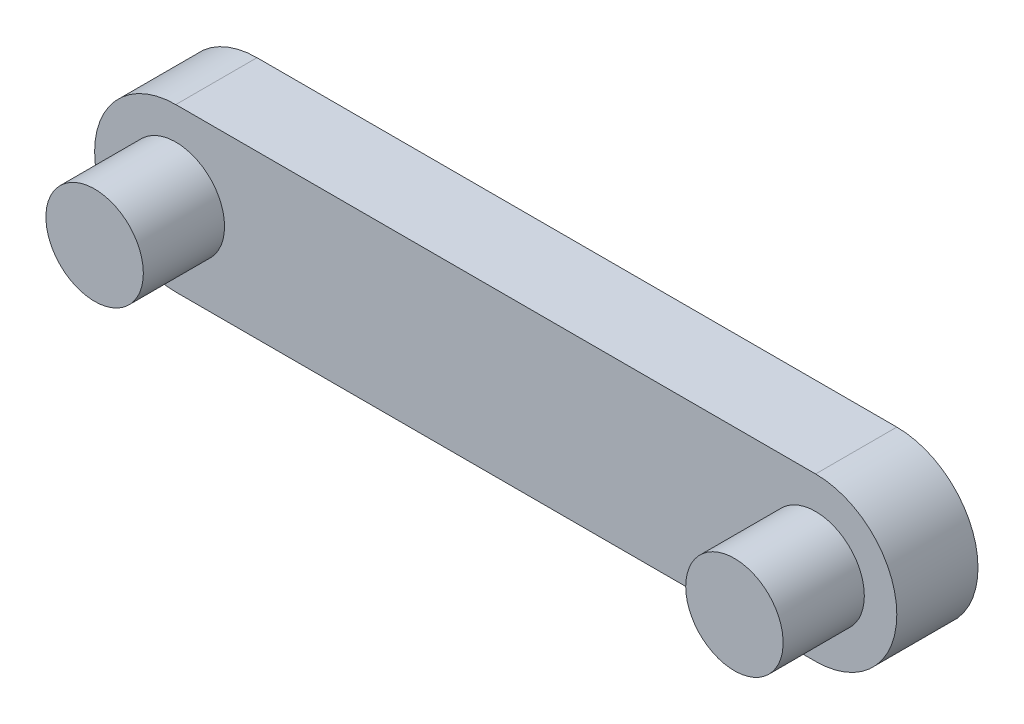
SolidWorks part; units mm, degrees
ref_plane "Front Plane" through (0, 0, 0) normal (0, 0, 1) x (1, 0, 0)
ref_plane "Top Plane" through (0, 0, 0) normal (0, 1, 0) x (1, 0, 0)
ref_plane "Right Plane" through (0, 0, 0) normal (1, 0, 0) x (0, 0, -1)
sketch "Sketch1" plane through (0, 0, 0) normal (0, 0, 1) x (1, 0, 0)
  line L0 (19.7, 0) -> (-19.7, 0) construction
  line L1 (19.7, -5) -> (-19.7, -5)
  line L2 (19.7, 5) -> (-19.7, 5)
  arc A0 (19.7, -5) -> (19.7, 5) centre (19.7, 0) ccw
  arc A1 (-19.7, 5) -> (-19.7, -5) centre (-19.7, 0) ccw
  circle A2 centre (19.7, 0) radius 3
  point P2 (0, 0)
  dimension "D2" = 5
  dimension "D3" = 6
  dimension "D1" = 39.4
extrude "Boss-Extrude1" add sketch "Sketch1" along normal blind 5
sketch "Sketch2" plane through (0, 0, 5) normal (0, 0, 1) x (1, 0, 0)
  circle A0 centre (-19.7, 0) radius 3
  dimension "D1" = 6
extrude "Boss-Extrude2" add sketch "Sketch2" along normal blind 5
sketch "Sketch3" plane through (0, 0, 0) normal (0, 0, -1) x (-1, 0, 0)
  circle A0 centre (-19.7, 0) radius 3
extrude "Boss-Extrude3" add sketch "Sketch3" against normal blind 10
